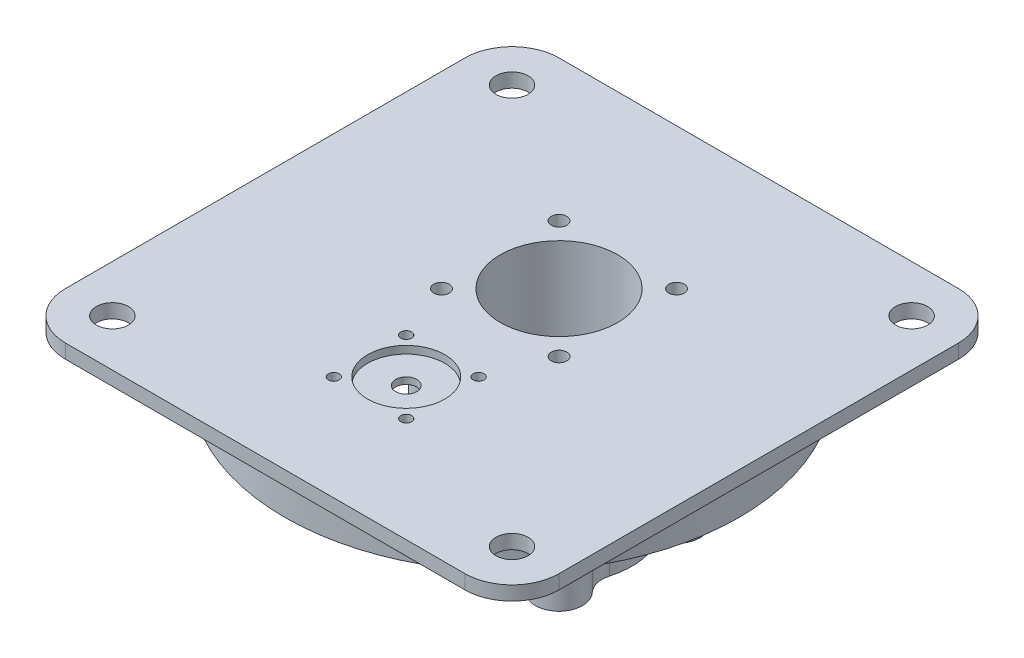
SolidWorks part; units mm, degrees
ref_plane "Front Plane" through (0, 0, 0) normal (0, 0, 1) x (1, 0, 0)
ref_plane "Top Plane" through (0, 0, 0) normal (0, 1, 0) x (1, 0, 0)
ref_plane "Right Plane" through (0, 0, 0) normal (1, 0, 0) x (0, 0, -1)
sketch "Sketch1" plane through (0, 0, 0) normal (0, 1, 0) x (1, 0, 0)
  line L1 (52.5, 52.5) -> (-52.5, 52.5)
  line L2 (52.5, 52.5) -> (52.5, -52.5)
  line L3 (52.5, -52.5) -> (-52.5, -52.5)
  line L4 (-52.5, 52.5) -> (-52.5, -52.5)
  line L5 (52.5, 52.5) -> (-52.5, -52.5) construction
  line L6 (52.5, -52.5) -> (-52.5, 52.5) construction
  point P0 (0, 0)
  dimension "D1" = 105
extrude "Boss-Extrude1" add sketch "Sketch1" along normal blind 3
sketch "Sketch3" plane through (0, 3, 0) normal (0, 1, 0) x (1, 0, 0)
  line L0 (0, 0) -> (0, -22.5) construction
  line L2 (7.7, -14.8) -> (-7.7, -14.8) construction
  line L3 (7.7, -14.8) -> (7.7, -30.2) construction
  line L4 (7.7, -30.2) -> (-7.7, -30.2) construction
  line L5 (-7.7, -14.8) -> (-7.7, -30.2) construction
  line L6 (7.7, -14.8) -> (-7.7, -30.2) construction
  line L7 (7.7, -30.2) -> (-7.7, -14.8) construction
  circle A0 centre (-7.7, -30.2) radius 1.15
  circle A1 centre (7.7, -30.2) radius 1.15
  circle A2 centre (7.7, -14.8) radius 1.15
  circle A3 centre (-7.7, -14.8) radius 1.15
  circle A4 centre (0, -22.5) radius 2.25
  dimension "D3" = 2.3
  dimension "D4" = 4.5
  dimension "D1" = 22.5
  dimension "D2" = 15.4
extrude "Cut-Extrude1" cut sketch "Sketch3" against normal through all
sketch "Sketch4" plane through (0, 3, 0) normal (0, 1, 0) x (1, 0, 0)
  circle A0 centre (0, -22.5) radius 8.2
  dimension "D1" = 16.4
extrude "Cut-Extrude2" cut sketch "Sketch4" against normal blind 1.6
sketch "Sketch5" plane through (0, 0, 0) normal (0, -1, 0) x (1, 0, 0)
  circle A0 centre (0, 0) radius 45.3
  circle A1 centre (0, 0) radius 48.3
  dimension "D1" = 90.6
  dimension "D2" = 3
extrude "Boss-Extrude3" add sketch "Sketch5" along normal blind 10
sketch "Sketch6" plane through (0, 0, 0) normal (0, -1, 0) x (1, 0, 0)
  line L0 (0, 0) -> (0, -35) construction
  circle A0 centre (0, 0) radius 35 construction
  circle A1 centre (0, -10) radius 12.5
  dimension "D1" = 70
  dimension "D3" = 25
  dimension "D2" = 10
extrude "Cut-Extrude3" cut sketch "Sketch6" against normal through all
sketch "Sketch7" plane through (0, 0, 0) normal (0, -1, 0) x (1, 0, 0)
  line L1 (12.5, -22.5) -> (-12.5, -22.5) construction
  line L2 (12.5, -22.5) -> (12.5, 2.5) construction
  line L3 (12.5, 2.5) -> (-12.5, 2.5) construction
  line L4 (-12.5, -22.5) -> (-12.5, 2.5) construction
  line L5 (12.5, -22.5) -> (-12.5, 2.5) construction
  line L6 (12.5, 2.5) -> (-12.5, -22.5) construction
  line L7 (10.15, 12.35) -> (-10.15, 12.35) construction
  line L8 (10.15, 12.35) -> (10.15, 32.65) construction
  line L9 (10.15, 32.65) -> (-10.15, 32.65) construction
  line L10 (-10.15, 12.35) -> (-10.15, 32.65) construction
  line L11 (10.15, 12.35) -> (-10.15, 32.65) construction
  line L12 (10.15, 32.65) -> (-10.15, 12.35) construction
  circle A0 centre (0, -10) radius 12.5 construction
  circle A1 centre (0, -10) radius 12.5
  circle A2 centre (-12.5, 2.5) radius 2.15 construction
  arc A3 (-7.6025, 3.5075) -> (-13.5075, -2.3975) centre (-12.5, 2.5) ccw
  arc A4 (13.5075, -2.3975) -> (7.6025, 3.5075) centre (12.5, 2.5) ccw
  arc A5 (7.6025, -23.5075) -> (13.5075, -17.6025) centre (12.5, -22.5) ccw
  arc A6 (-13.5075, -17.6025) -> (-7.6025, -23.5075) centre (-12.5, -22.5) ccw
  arc A7 (-13.5075, -2.3975) -> (-13.5075, -17.6025) centre (0, -10) ccw
  arc A8 (-7.6025, -23.5075) -> (7.6025, -23.5075) centre (0, -10) ccw
  arc A9 (13.5075, -17.6025) -> (13.5075, -2.3975) centre (0, -10) ccw
  arc A10 (7.6025, 3.5075) -> (-7.6025, 3.5075) centre (0, -10) ccw
  point P18 (0, 22.5)
  dimension "D2" = 4.3
  dimension "D3" = 10
  dimension "D4" = 3
  dimension "D1" = 25
  dimension "D5" = 20.3
extrude "Boss-Extrude4" add sketch "Sketch7" along normal blind 40.4
fillet "Fillet1" radius 5 8 edges at (-7.6025, -20.2, -23.5075) (-13.5075, -20.2, -17.6025) (13.5075, -20.2, -2.3975) (7.6025, -20.2, 3.5075) (-13.5075, -20.2, -2.3975) (7.6025, -20.2, -23.5075) (13.5075, -20.2, -17.6025) (-7.6025, -20.2, 3.5075)
sketch "Sketch8" plane through (0, -40.4, 0) normal (0, -1, 0) x (1, 0, 0)
  circle A0 centre (-12.5, -22.5) radius 2.15
  circle A1 centre (12.5, -22.5) radius 2.15
  circle A2 centre (-12.5, 2.5) radius 2.15
  circle A3 centre (12.5, 2.5) radius 2.15
  dimension "D1" = 4.3
extrude "Cut-Extrude4" cut sketch "Sketch8" against normal blind 10
sketch "Sketch9" plane through (0, -30.4, 0) normal (0, -1, 0) x (1, 0, 0)
  circle A0 centre (12.5, -22.5) radius 1.65
  circle A1 centre (-12.5, -22.5) radius 1.65
  circle A2 centre (-12.5, 2.5) radius 1.65
  circle A3 centre (12.5, 2.5) radius 1.65
  dimension "D1" = 3.3
extrude "Cut-Extrude5" cut sketch "Sketch9" against normal through all
fillet "Fillet2" radius 10 4 edges at (-52.5, 1.5, -52.5) (52.5, 1.5, -52.5) (52.5, 1.5, 52.5) (-52.5, 1.5, 52.5)
sketch "Sketch10" plane through (0, 0, 0) normal (0, -1, 0) x (1, 0, 0)
  circle A0 centre (-42.5, -42.5) radius 3.4195
  circle A1 centre (42.5, -42.5) radius 3.4195
  circle A2 centre (42.5, 42.5) radius 3.4195
  circle A3 centre (-42.5, 42.5) radius 3.4195
  dimension "D1" = 6.839
extrude "Cut-Extrude6" cut sketch "Sketch10" against normal through all
